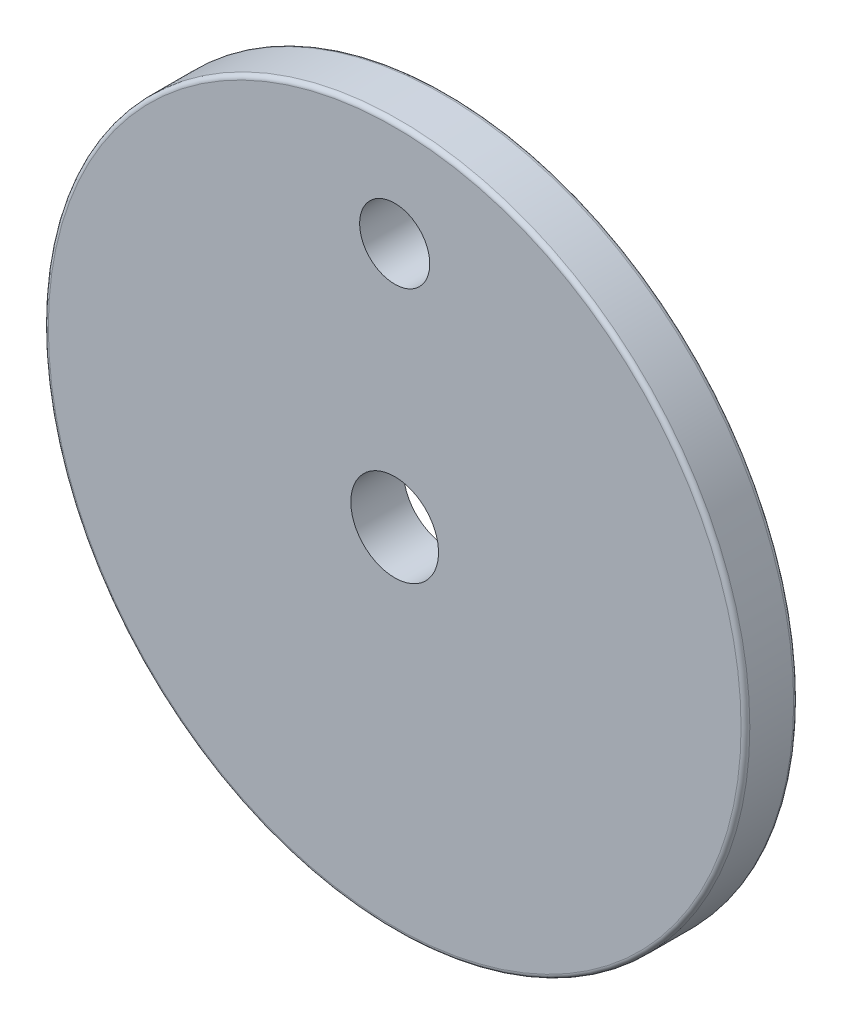
SolidWorks part; units mm, degrees
ref_plane "Front Plane" through (0, 0, 0) normal (0, 0, 1) x (1, 0, 0)
ref_plane "Top Plane" through (0, 0, 0) normal (0, 1, 0) x (1, 0, 0)
ref_plane "Right Plane" through (0, 0, 0) normal (1, 0, 0) x (0, 0, -1)
sketch "Sketch1" plane through (0, 0, 0) normal (0, 0, 1) x (1, 0, 0)
  line L0 (0, 0) -> (0, 355.6) construction
  circle A0 centre (0, 0) radius 508
  circle A1 centre (0, 0) radius 63.5
  circle A2 centre (0, 355.6) radius 50.8
  dimension "D1" = 1016
  dimension "D2" = 127
  dimension "D4" = 101.6
  dimension "D3" = 355.6
extrude "Boss-Extrude1" add sketch "Sketch1" along normal mid plane 76.2
fillet "Fillet1" radius 6.35 2 edges at (508, 0, -38.1) (508, 0, 38.1)
